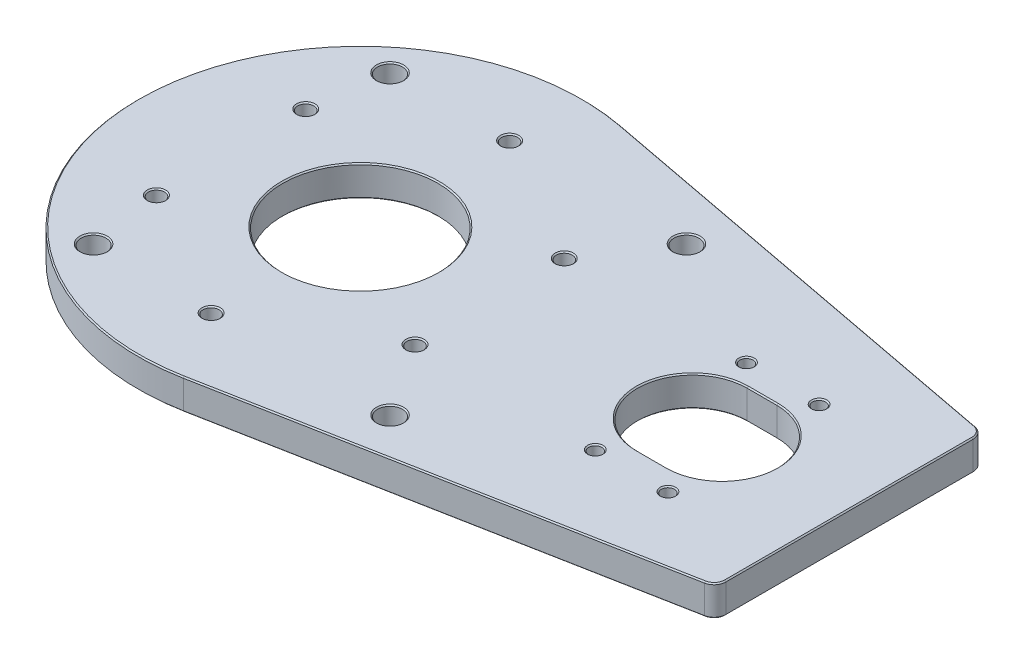
SolidWorks part; units mm, degrees
ref_plane "Front Plane" through (0, 0, 0) normal (0, 0, 1) x (1, 0, 0)
ref_plane "Top Plane" through (0, 0, 0) normal (0, 1, 0) x (1, 0, 0)
ref_plane "Right Plane" through (0, 0, 0) normal (1, 0, 0) x (0, 0, -1)
sketch "Sketch1" plane through (0, 0, 0) normal (0, 1, 0) x (1, 0, 0)
  line L0 (0, 0) -> (112, 0) construction
  line L1 (8.2987, 37.2569) -> (119.7682, 12.4279) construction
  line L2 (8.2987, -37.2569) -> (119.7682, -12.4279) construction
  line L3 (13.9957, 73.6826) -> (165, 45)
  line L4 (165, 45) -> (165, 0)
  line L5 (165, 0) -> (165, -45)
  line L6 (165, -45) -> (13.9957, -73.6826)
  line L7 (122, 0) -> (140.5, 0) construction
  line L8 (0, 0) -> (-75, 0) construction
  line L9 (122, 0) -> (112, 0) construction
  line L10 (122, -18.5) -> (112, -18.5)
  line L11 (122, 18.5) -> (112, 18.5)
  line L12 (117, 0) -> (117, 25.5) construction
  line L13 (117, 0) -> (117, -25.5) construction
  line L14 (117, -25.5) -> (104.75, -25.5) construction
  line L15 (117, -25.5) -> (129.25, -25.5) construction
  line L16 (140.5, 0) -> (165, 0) construction
  line L17 (0, 0) -> (0, -50) construction
  line L18 (0, -50) -> (-40, -50) construction
  line L19 (0, -50) -> (60, -50) construction
  circle A0 centre (0, 0) radius 38.17 construction
  circle A1 centre (117, 0) radius 12.7325 construction
  arc A2 (13.9957, 73.6826) -> (13.9957, -73.6826) centre (0, 0) ccw
  arc A3 (122, -18.5) -> (122, 18.5) centre (122, 0) ccw
  arc A4 (112, 18.5) -> (112, -18.5) centre (112, 0) ccw
  circle A5 centre (104.75, -25.5) radius 2.2
  circle A6 centre (129.25, -25.5) radius 2.2
  circle A7 centre (129.25, 25.5) radius 2.2
  circle A8 centre (104.75, 25.5) radius 2.2
  circle A10 centre (0, 50.35) radius 2.7
  circle A11 centre (43.6044, 25.175) radius 2.7
  circle A12 centre (-40, -50) radius 4.2
  circle A13 centre (43.6044, -25.175) radius 2.7
  circle A14 centre (60, -50) radius 4.2
  circle A15 centre (0, -50.35) radius 2.7
  circle A16 centre (60, 50) radius 4.2
  circle A17 centre (-43.6044, -25.175) radius 2.7
  circle A18 centre (-40, 50) radius 4.2
  circle A19 centre (-43.6044, 25.175) radius 2.7
  circle A20 centre (0, 0) radius 50.35 construction
  circle A21 centre (0, 0) radius 26.2
  arc A22 (161.7464, 45.618) -> (165, 41.6883) centre (161, 41.6883) cw
  arc A23 (161.7464, -45.618) -> (165, -41.6883) centre (161, -41.6883) ccw
  circle A24 centre (0, 0) radius 59.7991 construction
  point P18 (117, 0)
  point P56 (0, 0)
  dimension "D1" = 76.34
  dimension "D2" = 25.465
  dimension "D4" = 150
  dimension "D7" = 18.5
  dimension "D10" = 4.4
  dimension "D11" = 100.7
  dimension "D12" = 5.4
  dimension "D14" = 52.4
  dimension "D18" = 8.4
  dimension "D20" = 4
  dimension "D3" = 117
  dimension "D5" = 240
  dimension "D6" = 10
  dimension "D8" = 51
  dimension "D9" = 24.5
  dimension "D15" = 40
  dimension "D16" = 60
  dimension "D17" = 50
  dimension "D19" = 90
  dimension "D13" = 6
extrude "Boss-Extrude1" add sketch "Sketch1" along normal blind 10.3 contours L6 A23 L5 L4 A22 L3 A2 A21 A19 A16 A15 A14 A13 A12 A11 A10 A7 A6 A5 A4 L11 A3 L10 A8 A17 A18
sketch "Sketch2" plane through (0, 0, 0) normal (0, -1, 0) x (1, 0, 0)
  circle A0 centre (43.6044, -25.175) radius 5.2
  circle A1 centre (0, -50.35) radius 5.2
  circle A2 centre (-43.6044, -25.175) radius 5.2
  circle A3 centre (-43.6044, 25.175) radius 5.2
  circle A4 centre (0, 50.35) radius 5.2
  circle A5 centre (43.6044, 25.175) radius 5.2
  circle A6 centre (104.75, -25.5) radius 5.2
  circle A7 centre (129.25, -25.5) radius 5.2
  circle A8 centre (129.25, 25.5) radius 5.2
  circle A9 centre (104.75, 25.5) radius 5.2
  point P16 (0, 0)
  dimension "D1" = 10.4
  dimension "D2" = 6
extrude "Cut-Extrude2" cut sketch "Sketch2" against normal blind 5.2
chamfer "Chamfer1" distance 0.4 angle 45 60 edges at (-75, 10.3, 0) (87.871, 10.3, -59.6503) (164.0811, 10.3, -44.2392) (165, 10.3, 0) (164.0811, 10.3, 44.2392) (87.871, 10.3, 59.6503) (-40, 10.3, -45.8) (-43.6044, 10.3, 27.875) (104.75, 10.3, -23.3) (117, 10.3, 18.5) (140.5, 10.3, 0) (117, 10.3, -18.5) (93.5, 10.3, 0) (104.75, 10.3, 27.7) (129.25, 10.3, 27.7) (129.25, 10.3, -23.3) (0, 10.3, -47.65) (43.6044, 10.3, -22.475) (-40, 10.3, 54.2) (43.6044, 10.3, 27.875) (60, 10.3, 54.2) (0, 10.3, 53.05) (60, 10.3, -45.8) (-43.6044, 10.3, -22.475) (0, 10.3, 26.2) (164.0811, 0, 44.2392) (165, 0, 0) (164.0811, 0, -44.2392) (87.871, 0, -59.6503) (-75, 0, 0) (87.871, 0, 59.6503) (-40, 0, -45.8) (117, 0, -18.5) (140.5, 0, 0) (117, 0, 18.5) (93.5, 0, 0) (-40, 0, 54.2) (60, 0, 54.2) (60, 0, -45.8) (0, 0, 26.2) (43.6044, 0, -30.375) (104.75, 0, 20.3) (104.75, 0, -30.7) (0, 0, -55.55) (-43.6044, 0, -30.375) (-43.6044, 0, 19.975) (0, 0, 45.15) (43.6044, 0, 19.975) (129.25, 0, -30.7) (129.25, 0, 20.3) (129.25, 5.2, -27.7) (104.75, 5.2, -27.7) (129.25, 5.2, 23.3) (104.75, 5.2, 23.3) (43.6044, 5.2, 22.475) (43.6044, 5.2, -27.875) (0, 5.2, -53.05) (-43.6044, 5.2, -27.875) (-43.6044, 5.2, 22.475) (0, 5.2, 47.65)
